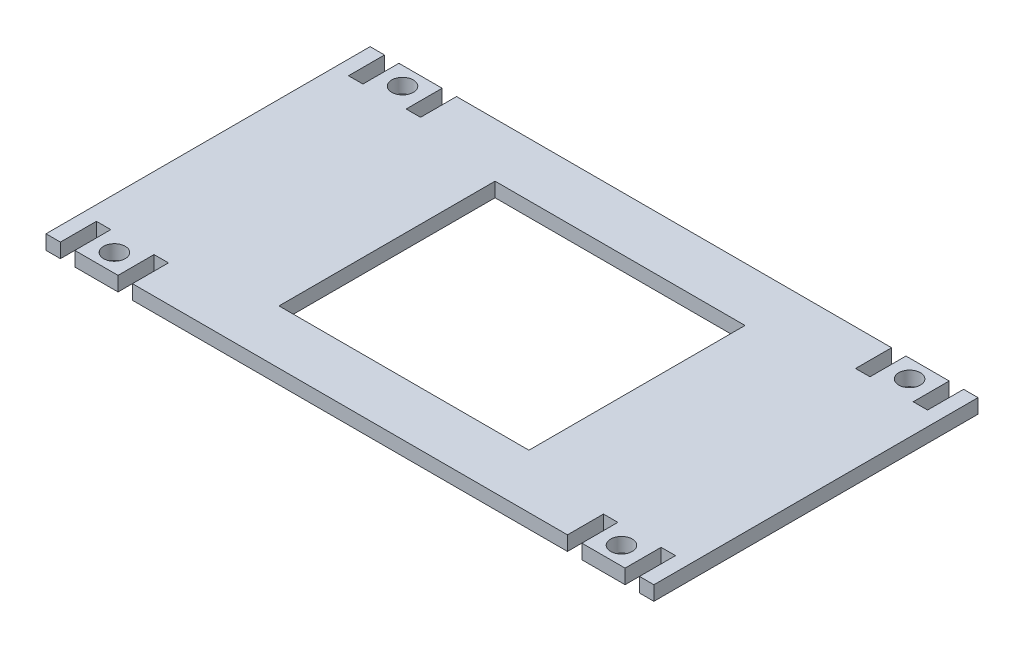
SolidWorks part; units mm, degrees
ref_plane "Front Plane" through (0, 0, 0) normal (0, 0, 1) x (1, 0, 0)
ref_plane "Top Plane" through (0, 0, 0) normal (0, 1, 0) x (1, 0, 0)
ref_plane "Right Plane" through (0, 0, 0) normal (1, 0, 0) x (0, 0, -1)
sketch "Sketch1" plane through (0, 0, 0) normal (0, 1, 0) x (1, 0, 0)
  line L0 (42.2, 45) -> (42.2, 0) construction
  line L1 (0, 0) -> (2, 0)
  line L2 (0, 0) -> (0, 45)
  line L3 (0, 45) -> (2, 45)
  line L4 (84.4, 0) -> (84.4, 45)
  line L5 (0, 22.5) -> (84.4, 22.5) construction
  line L6 (7, 45) -> (7, 42.5) construction
  line L7 (7, 42.5) -> (11, 42.5) construction
  line L9 (10, 40) -> (12, 40)
  line L10 (10, 40) -> (10, 45)
  line L12 (12, 40) -> (12, 45)
  line L13 (10, 40) -> (12, 45) construction
  line L14 (10, 45) -> (12, 40) construction
  line L15 (2, 40) -> (2, 45)
  line L16 (4, 40) -> (2, 40)
  line L17 (4, 40) -> (4, 45)
  line L19 (72.4, 40) -> (72.4, 45)
  line L20 (74.4, 40) -> (72.4, 40)
  line L21 (74.4, 40) -> (74.4, 45)
  line L22 (80.4, 40) -> (80.4, 45)
  line L23 (80.4, 40) -> (82.4, 40)
  line L24 (82.4, 40) -> (82.4, 45)
  line L27 (12, 5) -> (12, 0)
  line L28 (10, 5) -> (12, 5)
  line L29 (10, 5) -> (10, 0)
  line L30 (4, 5) -> (4, 0)
  line L31 (4, 5) -> (2, 5)
  line L32 (2, 5) -> (2, 0)
  line L35 (82.4, 5) -> (82.4, 0)
  line L36 (80.4, 5) -> (82.4, 5)
  line L37 (80.4, 5) -> (80.4, 0)
  line L38 (74.4, 5) -> (74.4, 0)
  line L39 (74.4, 5) -> (72.4, 5)
  line L40 (72.4, 5) -> (72.4, 0)
  line L42 (4, 0) -> (10, 0)
  line L43 (12, 0) -> (72.4, 0)
  line L44 (4, 45) -> (10, 45)
  line L45 (12, 45) -> (72.4, 45)
  line L46 (82.4, 45) -> (84.4, 45)
  line L47 (74.4, 45) -> (80.4, 45)
  line L48 (82.4, 0) -> (84.4, 0)
  line L49 (74.4, 0) -> (80.4, 0)
  circle A0 centre (7, 42.5) radius 1.5
  circle A1 centre (77.4, 42.5) radius 1.5
  circle A2 centre (7, 2.5) radius 1.5
  circle A3 centre (77.4, 2.5) radius 1.5
  dimension "D3" = 3
  dimension "D1" = 84.4
  dimension "D2" = 45
  dimension "D4" = 2
  dimension "D5" = 5
  dimension "D7" = 2
  dimension "D8" = 6
extrude "Boss-Extrude1" add sketch "Sketch1" along normal blind 2
sketch "Sketch2" plane through (0, 2, 0) normal (0, 1, 0) x (1, 0, 0)
  line L0 (42.2, 45) -> (42.2, 0) construction
  line L1 (72.4, 45) -> (12, 45) construction
  line L2 (12, 0) -> (72.4, 0) construction
  line L3 (0, 22.5) -> (42.2, 22.5) construction
  line L4 (0, 45) -> (0, 0) construction
  line L6 (59.55, 7.5) -> (24.85, 7.5)
  line L7 (59.55, 7.5) -> (59.55, 37.5)
  line L8 (59.55, 37.5) -> (24.85, 37.5)
  line L9 (24.85, 7.5) -> (24.85, 37.5)
  line L10 (59.55, 7.5) -> (24.85, 37.5) construction
  line L11 (59.55, 37.5) -> (24.85, 7.5) construction
  dimension "D1" = 34.7
  dimension "D2" = 30
extrude "Cut-Extrude1" cut sketch "Sketch2" against normal blind 10
